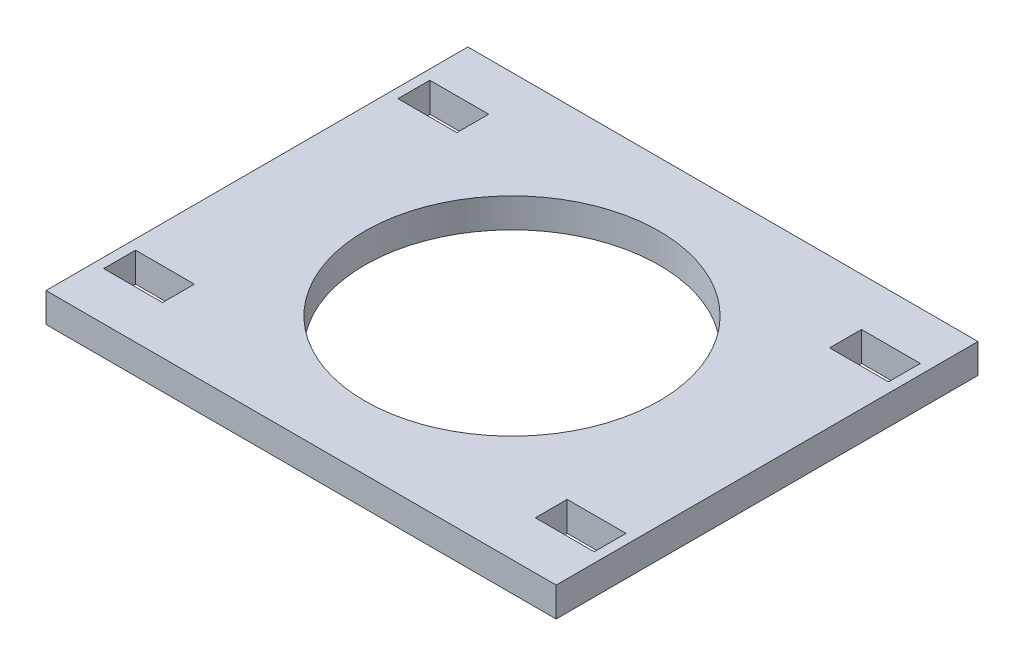
SolidWorks part; units mm, degrees
ref_plane "Front Plane" through (0, 0, 0) normal (0, 0, 1) x (1, 0, 0)
ref_plane "Top Plane" through (0, 0, 0) normal (0, 1, 0) x (1, 0, 0)
ref_plane "Right Plane" through (0, 0, 0) normal (1, 0, 0) x (0, 0, -1)
sketch "Sketch1" plane through (0, 0, 0) normal (0, 1, 0) x (1, 0, 0)
  line L1 (-52, -43) -> (52, -43)
  line L2 (-52, -43) -> (-52, 43)
  line L3 (-52, 43) -> (52, 43)
  line L4 (52, -43) -> (52, 43)
  line L5 (-50, -33.25) -> (-38, -33.25)
  line L6 (-50, -33.25) -> (-50, -26.75)
  line L7 (-50, -26.75) -> (-38, -26.75)
  line L8 (-38, -33.25) -> (-38, -26.75)
  line L9 (-50, 26.75) -> (-38, 26.75)
  line L10 (-50, 26.75) -> (-50, 33.25)
  line L11 (-50, 33.25) -> (-38, 33.25)
  line L12 (-38, 26.75) -> (-38, 33.25)
  line L13 (38, -33.25) -> (50, -33.25)
  line L14 (38, -33.25) -> (38, -26.75)
  line L15 (38, -26.75) -> (50, -26.75)
  line L16 (50, -33.25) -> (50, -26.75)
  line L17 (38, 26.75) -> (50, 26.75)
  line L18 (38, 26.75) -> (38, 33.25)
  line L19 (38, 33.25) -> (50, 33.25)
  line L20 (50, 26.75) -> (50, 33.25)
  circle A0 centre (0, 0) radius 30
extrude "Motor_Cradle_Plate" add sketch "Sketch1" along normal blind 6
equation "\"ValveDiameter\" = 50mm"
equation "\"MotorGearTeeth\" = 40"
equation "\"OutputGearTeeth\" = 80"
equation "\"GearModule\" = 1.5mm"
equation "\"PressureAngle\" = 20deg"
equation "\"GearCenterDistance\" = 90mm"
equation "\"GearWidth\" = 18mm"
equation "\"OutputShaftDiameter\" = 20mm"
equation "\"BearingOD\" = 47mm"
equation "\"BearingWidth\" = 14mm"
equation "\"PlateThickness\" = 6mm"
equation "\"ValveRotation\" = 90deg"
